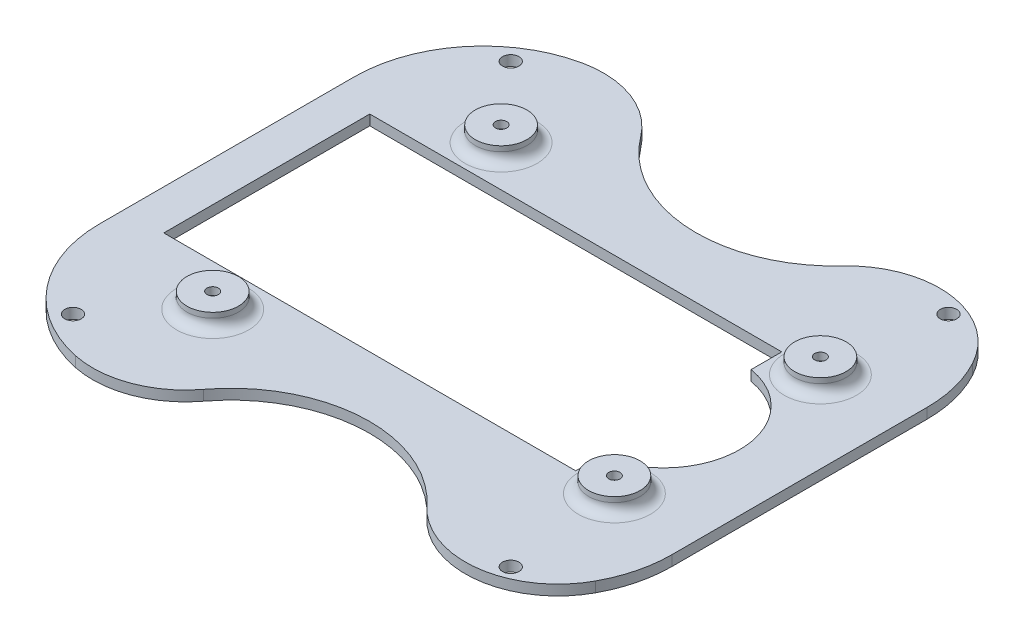
SolidWorks part; units mm, degrees
ref_plane "Front Plane" through (0, 0, 0) normal (0, 0, 1) x (1, 0, 0)
ref_plane "Top Plane" through (0, 0, 0) normal (0, 1, 0) x (1, 0, 0)
ref_plane "Right Plane" through (0, 0, 0) normal (1, 0, 0) x (0, 0, -1)
sketch "Sketch1" plane through (0, 0, 0) normal (0, 1, 0) x (1, 0, 0)
  line L0 (-43.0059, 42.5384) -> (41.9941, 42.5384) construction
  line L1 (-55.5968, 49.7546) -> (55.5968, 49.7546)
  line L2 (-55.5968, 49.7546) -> (-55.5968, -49.7546)
  line L3 (-55.5968, -49.7546) -> (55.5968, -49.7546)
  line L4 (55.5968, 49.7546) -> (55.5968, -49.7546)
  line L5 (41.9941, 42.5384) -> (41.9941, -42.4616) construction
  line L6 (41.9941, -42.4616) -> (-43.0059, -42.4616) construction
  line L7 (-43.0059, -42.4616) -> (-43.0059, 42.5384) construction
  line L8 (41.9941, 42.5384) -> (-43.0059, -42.4616) construction
  circle A8 centre (-43.0059, 42.5384) radius 1.6
  circle A9 centre (41.9941, 42.5384) radius 1.6
  circle A10 centre (41.9941, -42.4616) radius 1.6
  circle A11 centre (-43.0059, -42.4616) radius 1.6
  point P0 (0, 49.7546)
  point P1 (-55.5968, 0)
  dimension "D1" = 3.2
  dimension "D2" = 85
extrude "Boss-Extrude1" add sketch "Sketch1" along normal blind 2
sketch "Sketch2" plane through (0, 2, 0) normal (0, 1, 0) x (1, 0, 0)
  line L0 (39.7243, 19.9361) -> (39.7243, -20.0639) construction
  line L1 (39.7243, -0.0639) -> (-32.6127, -0.0639) construction
  circle A0 centre (-30.2757, 27.9361) radius 5
  circle A1 centre (39.7243, 19.9361) radius 5
  circle A2 centre (39.7243, -20.0639) radius 5
  circle A3 centre (-30.2757, -28.0639) radius 5
  dimension "D1" = 10
extrude "Boss-Extrude2" add sketch "Sketch2" along normal blind 3
sketch "Sketch3" plane through (0, 5, 0) normal (0, 1, 0) x (1, 0, 0)
  circle A0 centre (-30.2757, 27.9361) radius 1.1
  circle A1 centre (39.7243, 19.9361) radius 1.1
  circle A2 centre (39.7243, -20.0639) radius 1.1
  circle A3 centre (-30.2757, -28.0639) radius 1.1
  dimension "D1" = 2.2
extrude "Cut-Extrude2" cut sketch "Sketch3" against normal through all both and the other way through all
sketch "Sketch4" plane through (0, 0, 0) normal (0, -1, 0) x (1, 0, 0)
  circle A0 centre (-30.2757, 28.0639) radius 3.5
  circle A1 centre (39.7243, 20.0639) radius 3.5
  circle A2 centre (39.7243, -19.9361) radius 3.5
  circle A3 centre (-30.2757, -27.9361) radius 3.5
  dimension "D1" = 7
extrude "Cut-Extrude3" cut sketch "Sketch4" against normal blind 3.5 and the other way through all
fillet "Fillet1" radius 25 4 edges at (55.5968, 1, -49.7546) (55.5968, 1, 49.7546) (-55.5968, 1, 49.7546) (-55.5968, 1, -49.7546)
sketch "Sketch5" plane through (0, 2, 0) normal (0, 1, 0) x (1, 0, 0)
  line L1 (-47.8383, 20) -> (32.1617, 20)
  line L2 (-47.8383, 20) -> (-47.8383, -20)
  line L3 (-47.8383, -20) -> (32.1617, -20)
  line L4 (32.1617, 20) -> (32.1617, -20)
  point P4 (32.1617, 0)
  dimension "D1" = 40
  dimension "D2" = 80
extrude "Cut-Extrude4" cut sketch "Sketch5" against normal through all both and the other way through all contours L2 L1 L4 L3
sketch "Sketch6" plane through (0, 2, 0) normal (0, 1, 0) x (1, 0, 0)
  line L0 (30.5968, 49.7546) -> (-30.5968, 49.7546) construction
  line L1 (0, 0) -> (69.9318, 0) construction
  line L2 (-21.585, -49.7546) -> (29.2577, -49.7546)
  line L3 (-21.585, 49.7546) -> (29.2577, 49.7546)
  arc A0 (-21.585, 49.7546) -> (29.2577, 49.7546) centre (3.8363, 58.6331) ccw
  arc A1 (-21.585, -49.7546) -> (29.2577, -49.7546) centre (3.8363, -58.6331) cw
extrude "Cut-Extrude5" cut sketch "Sketch6" against normal through all both and the other way through all
sketch "Sketch7" plane through (0, 2, 0) normal (0, 1, 0) x (1, 0, 0)
  line L0 (32.1617, 20) -> (32.1617, -20) construction
  line L1 (32.1617, 14.0418) -> (32.1617, -15.1351)
  arc A0 (32.1617, 14.0418) -> (32.1617, -15.1351) centre (29.7305, -0.5466) cw
extrude "Cut-Extrude6" cut sketch "Sketch7" against normal through all both and the other way through all
fillet "Fillet3" radius 2 4 edges at (-30.2757, 2, -22.9361) (-30.2757, 2, 33.0639) (39.7243, 2, 25.0639) (39.7243, 2, -14.9361)
fillet "Fillet4" radius 18 4 edges at (-21.585, 1, 49.7546) (29.2577, 1, 49.7546) (29.2577, 1, -49.7546) (-21.585, 1, -49.7546)
